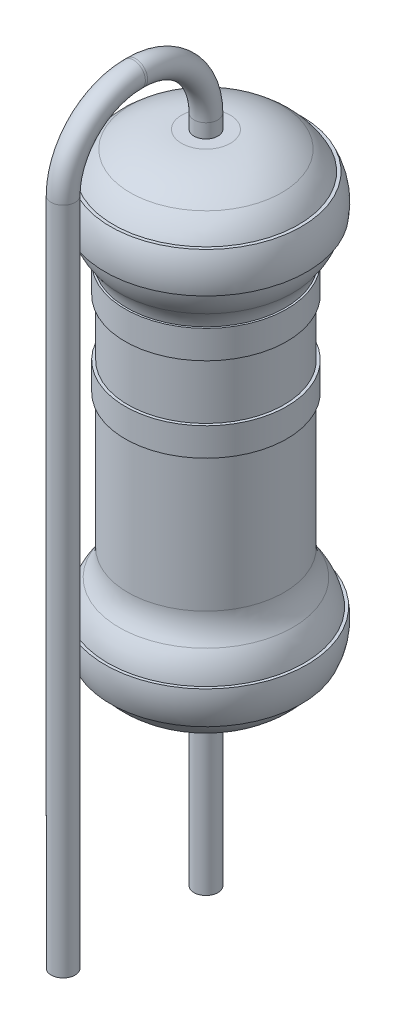
SolidWorks part; units mm, degrees
ref_plane "Front Plane" through (0, 0, 0) normal (0, 0, 1) x (1, 0, 0)
ref_plane "Top Plane" through (0, 0, 0) normal (0, 1, 0) x (1, 0, 0)
ref_plane "Right Plane" through (0, 0, 0) normal (1, 0, 0) x (0, 0, -1)
sketch "Sketch1" plane through (0, 0, 0) normal (1, 0, 0) x (0, 0, -1)
  line L0 (0, 9.1448) -> (0, -9.7229) construction
  line L1 (-2.775, 0) -> (-11.1157, 0) construction
  line L2 (-2.775, -4.2308) -> (-2.775, 0.55)
  line L3 (-0.8678, 8.65) -> (0, 8.65)
  line L4 (-3.5, 7.35) -> (-3.5, 7.1073) construction
  line L5 (-0.8678, -8.65) -> (0, -8.65)
  line L6 (0, -8.65) -> (0, 8.65)
  line L7 (-3.2866, 7.35) -> (-3.3987, 7.35)
  line L8 (-3.4879, 6.05) -> (-3.5894, 6.05)
  line L9 (-3.5894, 6.05) -> (-4.554, 6.05) construction
  line L10 (-3.3987, 7.35) -> (-3.7612, 7.35) construction
  line L11 (-3.5, 7.1073) -> (-3.5, 10.3125) construction
  line L12 (-3.5, 6.6794) -> (-3.5, 7.35) construction
  line L13 (0, 6.05) -> (-3.4879, 6.05) construction
  line L14 (-2.875, 4.55) -> (-2.8093, 4.55)
  line L15 (-2.875, 3.55) -> (-2.775, 3.55)
  line L16 (-2.875, 1.55) -> (-2.775, 1.55)
  line L17 (-2.875, 0.55) -> (-2.775, 0.55)
  line L18 (-2.875, 4.55) -> (-2.875, 3.55)
  line L19 (-2.875, 3.55) -> (-2.875, 1.55) construction
  line L20 (-2.875, 1.55) -> (-2.875, 0.55)
  line L21 (-2.775, 3.55) -> (-2.775, 4.2308) construction
  line L22 (-2.775, 0.55) -> (-2.775, 1.55) construction
  line L23 (-2.775, 1.55) -> (-2.775, 3.55)
  line L24 (-3.4879, -6.05) -> (-3.5894, -6.05)
  line L25 (-3.2866, -7.35) -> (-3.3987, -7.35)
  line L26 (-2.8093, 4.55) -> (-2.5539, 4.55) construction
  line L27 (-0.3921, 4.55) -> (0, 4.55) construction
  line L28 (-2.5539, 4.55) -> (-0.3921, 4.55) construction
  line L29 (-2.775, 3.55) -> (0, 3.55) construction
  line L30 (-2.775, 1.55) -> (0, 1.55) construction
  line L31 (-2.775, 0.55) -> (0, 0.55) construction
  line L32 (0, 0) -> (-2.775, 0) construction
  arc A0 (-3.0896, 5.15) -> (-3.4879, 6.05) centre (-1.473, 6.4035) cw
  arc A1 (-2.6958, 8.0435) -> (-0.8678, 8.65) centre (-0.8678, 5.592) cw
  arc A2 (-2.8093, 4.55) -> (-3.0896, 5.15) centre (-4.275, 4.2308) ccw
  arc A3 (-2.775, -4.2308) -> (-3.0896, -5.15) centre (-4.275, -4.2308) cw
  arc A4 (-3.0896, -5.15) -> (-3.4879, -6.05) centre (-1.473, -6.4035) ccw
  arc A5 (-2.6958, -8.0435) -> (-0.8678, -8.65) centre (-0.8678, -5.592) ccw
  arc A6 (-3.5894, 6.05) -> (-3.3987, 7.35) centre (-1.473, 6.4035) cw
  arc A7 (-3.1686, 5.0887) -> (-3.5894, 6.05) centre (-1.473, 6.4035) cw construction
  arc A8 (-3.1686, 5.0887) -> (-2.7556, 8.1237) centre (-1.473, 6.4035) cw construction
  arc A9 (-3.5, 7.1073) -> (-2.7556, 8.1237) centre (-1.473, 6.4035) cw construction
  arc A10 (-3.5, 6.6794) -> (-3.2866, 7.35) centre (-1.473, 6.4035) cw construction
  arc A11 (-3.2866, 7.35) -> (-2.6958, 8.0435) centre (-1.473, 6.4035) cw
  arc A12 (-3.0896, 5.15) -> (-2.6958, 8.0435) centre (-1.473, 6.4035) cw construction
  arc A13 (-3.4879, 6.05) -> (-3.5, 6.6794) centre (-1.473, 6.4035) cw construction
  arc A14 (-3.3987, 7.35) -> (0, 4.8434) centre (-1.473, 6.4035) cw construction
  arc A15 (-2.775, 4.2308) -> (-2.8093, 4.55) centre (-4.275, 4.2308) ccw construction
  arc A16 (-3.5894, -6.05) -> (-3.3987, -7.35) centre (-1.473, -6.4035) ccw
  arc A17 (-2.5539, 4.55) -> (-2.8808, 4.7843) centre (-1.473, 6.4035) cw construction
  arc A18 (-2.8808, 4.7843) -> (-3.5, 7.1073) centre (-1.473, 6.4035) cw construction
  arc A19 (-0.3921, 4.55) -> (-2.5539, 4.55) centre (-1.473, 6.4035) cw construction
  arc A20 (0, 4.8434) -> (-0.3921, 4.55) centre (-1.473, 6.4035) cw construction
  arc A21 (-3.4879, -6.05) -> (-3.2866, -7.35) centre (-1.473, -6.4035) ccw construction
  arc A22 (-3.2866, -7.35) -> (-2.6958, -8.0435) centre (-1.473, -6.4035) ccw
  point P17 (-2.775, 0)
  point P44 (0, 0)
  point P45 (0, 0)
  dimension "D1" = 17.3
  dimension "D2" = 1.5
  dimension "D3" = 10.3
  dimension "D4" = 5.55
  dimension "D5" = 3.5
  dimension "D6" = 0.1
  dimension "D7" = 1.3
  dimension "D8" = 1.3
  dimension "D9" = 1.5
  dimension "D10" = 1
  dimension "D11" = 2
  dimension "D12" = 1
  dimension "D13" = 0.1
revolve "Revolve1" add sketch "Sketch1" angle 360 about L6
sketch "Sketch2" plane through (0, 0, 0) normal (1, 0, 0) x (0, 0, -1)
  line L0 (0, 0) -> (0, 9.15)
  line L1 (-2.5, 11.65) -> (-2.58, 11.65)
  line L2 (-5.08, 9.15) -> (-5.08, -14.65)
  line L3 (0, 0) -> (0, -14.65)
  line L4 (0, -8.65) -> (5.2619, -8.65) construction
  line L5 (-0.8678, -8.65) -> (0.8678, -8.65) construction
  line L6 (0, 8.65) -> (4.2478, 8.65) construction
  line L7 (0.8678, 8.65) -> (-0.8678, 8.65) construction
  arc A0 (-5.08, 9.15) -> (-2.58, 11.65) centre (-2.58, 9.15) cw
  arc A1 (-2.5, 11.65) -> (0, 9.15) centre (-2.5, 9.15) cw
  point P18 (0, 11.65)
  point P19 (-5.08, -14.65)
  point P20 (0, 0)
  dimension "D4" = 2.5
  dimension "D1" = 5.08
  dimension "D2" = 3
  dimension "D3" = 6
sweep "Sweep1" add path "Sketch2" circular profile diameter 0.85 parameters "D3"=0.85
